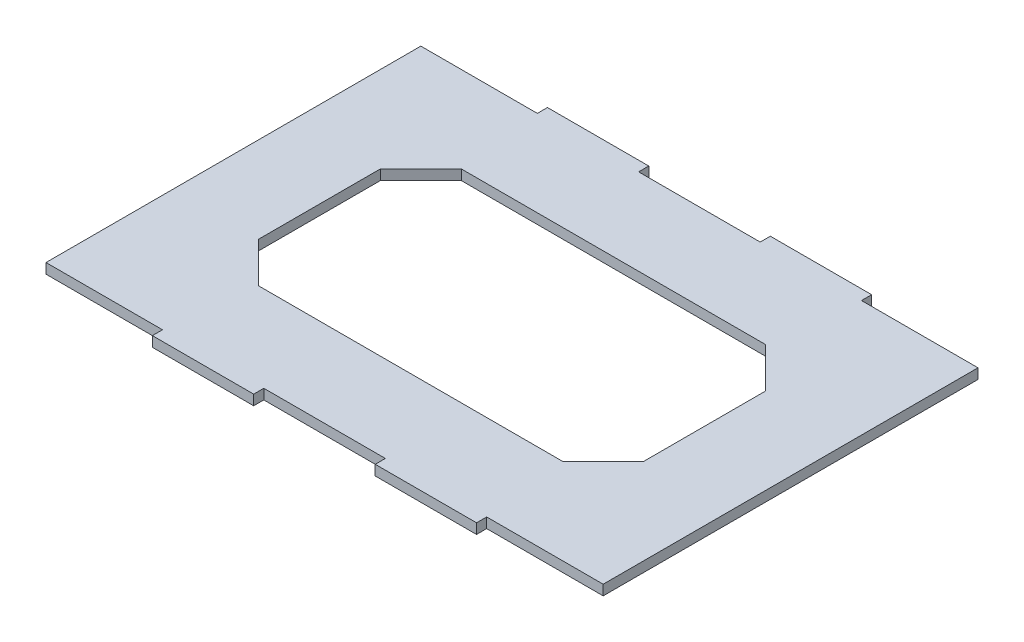
SolidWorks part; units mm, degrees
ref_plane "Plan de face" through (0, 0, 0) normal (0, 0, 1) x (1, 0, 0)
ref_plane "Plan de dessus" through (0, 0, 0) normal (0, 1, 0) x (1, 0, 0)
ref_plane "Plan de droite" through (0, 0, 0) normal (1, 0, 0) x (0, 0, -1)
sketch "Esquisse1" plane through (0, 0, 0) normal (0, 1, 0) x (1, 0, 0)
  line L0 (0, 0) -> (550, 0) construction
  line L1 (550, 0) -> (550, 10) construction
  line L2 (550, 10) -> (0, 10) construction
  line L3 (0, 10) -> (0, 0) construction
  line L4 (0, 10) -> (115, 10)
  line L5 (115, 10) -> (115, 0)
  line L6 (115, 0) -> (215, 0)
  line L7 (215, 0) -> (215, 10)
  line L8 (215, 10) -> (335, 10)
  line L9 (335, 10) -> (335, 0)
  line L10 (335, 0) -> (435, 0)
  line L11 (435, 0) -> (435, 10)
  line L12 (435, 10) -> (550, 10)
  line L13 (275, 10) -> (275, 0) construction
  line L14 (0, 10) -> (0, 380)
  line L15 (0, 195) -> (550, 195) construction
  line L16 (550, 380) -> (550, 10)
  line L17 (435, 380) -> (550, 380)
  line L18 (435, 390) -> (435, 380)
  line L19 (335, 390) -> (435, 390)
  line L20 (335, 380) -> (335, 390)
  line L21 (215, 380) -> (335, 380)
  line L22 (215, 390) -> (215, 380)
  line L23 (115, 390) -> (215, 390)
  line L24 (115, 380) -> (115, 390)
  line L25 (0, 380) -> (115, 380)
  line L26 (85, 135) -> (125, 95)
  line L27 (125, 295) -> (425, 295)
  line L28 (85, 255) -> (85, 135)
  line L29 (125, 95) -> (425, 95)
  line L30 (465, 255) -> (465, 135)
  line L31 (425, 95) -> (465, 135)
  line L32 (425, 295) -> (465, 255)
  line L33 (85, 255) -> (125, 295)
  point P27 (85, 295)
  point P28 (465, 95)
  point P29 (85, 95)
  point P30 (465, 295)
  point P31 (465, 195)
  dimension "D1" = 120
  dimension "D2" = 10
  dimension "D3" = 550
  dimension "D4" = 100
  dimension "D5" = 100
  dimension "D6" = 195
  dimension "D7" = 85
  dimension "D8" = 85
  dimension "D9" = 85
  dimension "D10" = 85
extrude "Boss.-Extru.1" add sketch "Esquisse1" along normal blind 10
